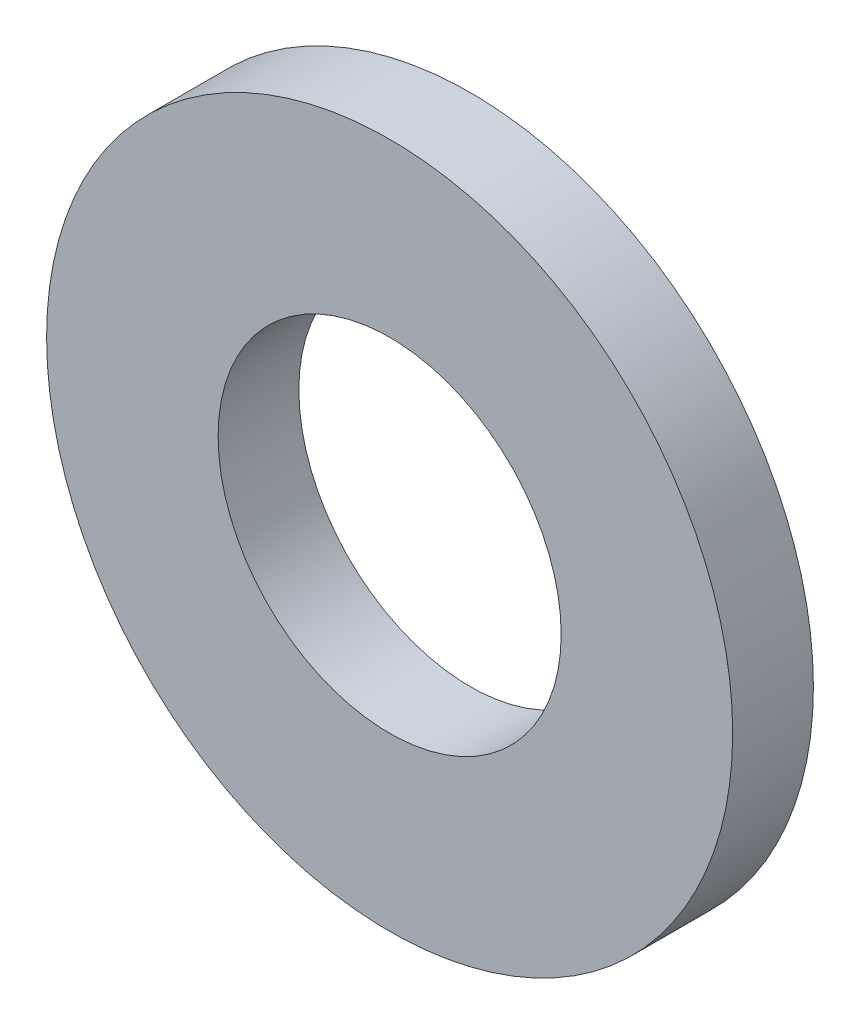
SolidWorks part; units mm, degrees
ref_plane "Front Plane" through (0, 0, 0) normal (0, 0, 1) x (1, 0, 0)
ref_plane "Top Plane" through (0, 0, 0) normal (0, 1, 0) x (1, 0, 0)
ref_plane "Right Plane" through (0, 0, 0) normal (1, 0, 0) x (0, 0, -1)
sketch "Sketch1" plane through (0, 0, 0) normal (0, 0, 1) x (1, 0, 0)
  circle A0 centre (0, 0) radius 8.5
  circle A1 centre (0, 0) radius 4.25
  dimension "D1" = 17
  dimension "D2" = 8.5
extrude "Boss-Extrude1" add sketch "Sketch1" along normal blind 2
